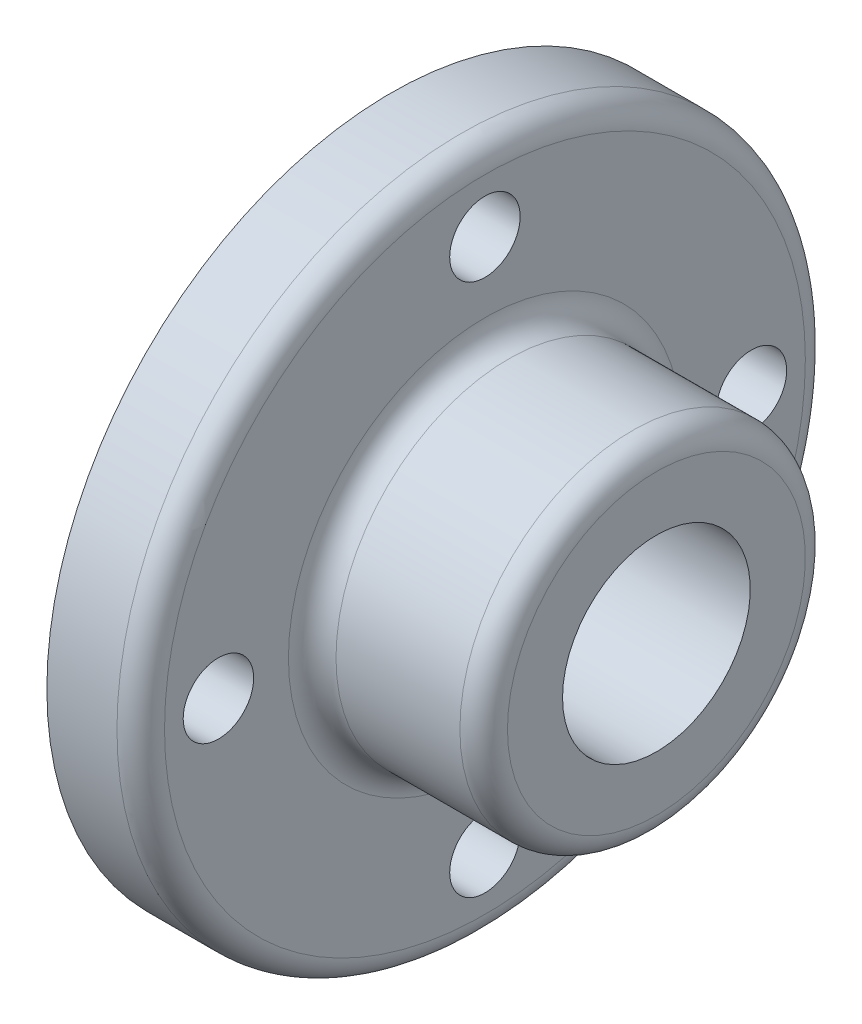
SolidWorks part; units mm, degrees
ref_plane "Front Plane" through (0, 0, 0) normal (0, 0, 1) x (1, 0, 0)
ref_plane "Top Plane" through (0, 0, 0) normal (0, 1, 0) x (1, 0, 0)
ref_plane "Right Plane" through (0, 0, 0) normal (1, 0, 0) x (0, 0, -1)
sketch "Sketch1" plane through (0, 0, 0) normal (0, 0, 1) x (1, 0, 0)
  line L0 (-88.7714, 0) -> (118.4797, 0) construction
  line L8 (-36.322, 35.052) -> (-1.524, 35.052)
  line L9 (-36.322, 69.85) -> (-36.322, 35.052)
  line L10 (-55.372, 69.85) -> (-36.322, 69.85)
  line L11 (-55.372, 0) -> (-55.372, 69.85)
  line L12 (-1.524, 0) -> (-55.372, 0)
  line L13 (-1.524, 35.052) -> (-1.524, 0)
  dimension "D1" = 139.7
  dimension "D2" = 70.104
  dimension "D3" = 19.05
  dimension "D4" = 53.848
revolve "Revolve1" add sketch "Sketch1" angle 360 about L0
draft "Draft6" [suppressed] draft angle 3 neutral plane "Right Plane" faces to draft 3 parameters "D1"=3
draft "Draft7" [suppressed] type of draft neutral plane draft angle 3 neutral plane "Right Plane" faces to draft 1 parameters "D1"=3
sketch "Sketch4" plane through (-55.372, 0, 0) normal (-1, 0, 0) x (0, 0, 1)
  circle A0 centre (0, 0) radius 19.05
  dimension "D1" = 38.1
extrude "Cut-Extrude3" cut sketch "Sketch4" against normal through all
sketch "Sketch6" plane through (-55.372, 0, 0) normal (-1, 0, 0) x (0, 0, 1)
  line L0 (0, 72.9012) -> (0, -79.4467) construction
  circle A0 centre (0, 0) radius 53.848 construction
  circle A1 centre (0, 54.0827) radius 7.1501
  dimension "D1" = 107.696
  dimension "D2" = 14.3002
extrude "Cut-Extrude5" cut sketch "Sketch6" against normal through all
pattern_circular "CirPattern2" count 4 over 360 about axis through (0, 0, 0) along (1, 0, 0) of "Cut-Extrude5"
fillet "Fillet1" radius 4.826 3 edges at (-36.322, 0, 69.85) (-36.322, 0, 35.052) (-1.524, 0, 35.052)
draft "Draft11" [suppressed] draft angle 3 neutral plane "Right Plane" faces to draft 1 parameters "D1"=3
